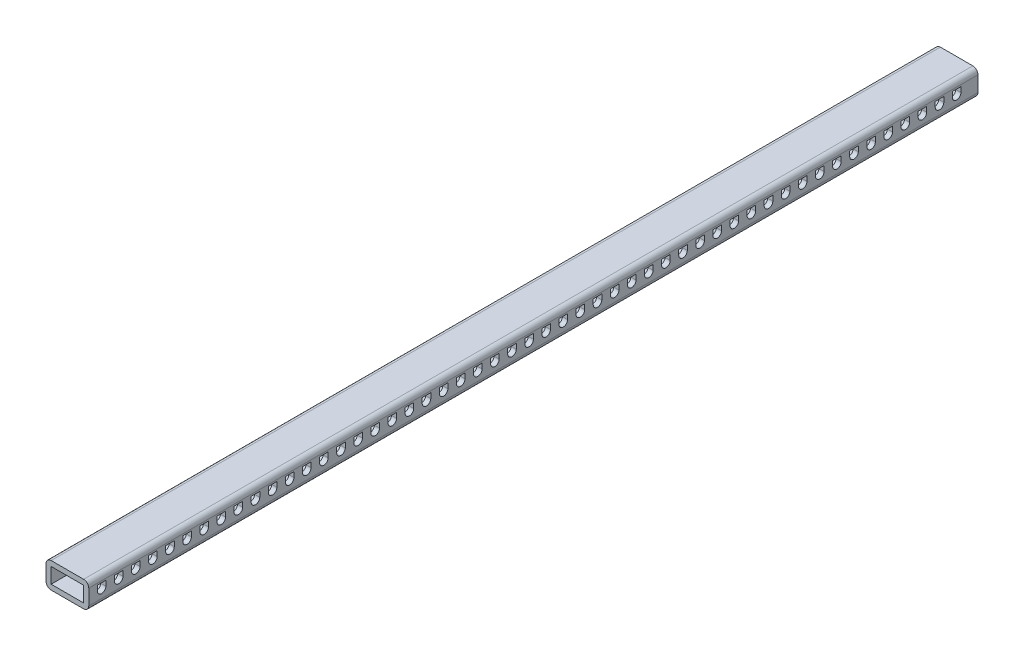
SolidWorks part; units mm, degrees
ref_plane "Front Plane" through (0, 0, 0) normal (0, 0, 1) x (1, 0, 0)
ref_plane "Top Plane" through (0, 0, 0) normal (0, 1, 0) x (1, 0, 0)
ref_plane "Right Plane" through (0, 0, 0) normal (1, 0, 0) x (0, 0, -1)
sketch "Sketch1" plane through (0, 0, 0) normal (0, 0, 1) x (1, 0, 0)
  line L1 (-12.5, 7.5) -> (12.5, 7.5)
  line L2 (-12.5, 7.5) -> (-12.5, -7.5)
  line L3 (-12.5, -7.5) -> (12.5, -7.5)
  line L4 (12.5, 7.5) -> (12.5, -7.5)
  line L5 (-12.5, 7.5) -> (12.5, -7.5) construction
  line L6 (-12.5, -7.5) -> (12.5, 7.5) construction
  point P0 (0, 0)
  dimension "D1" = 25
  dimension "D2" = 15
extrude "Boss-Extrude1" add sketch "Sketch1" along normal blind 520
sketch "Sketch2" plane through (0, 0, 520) normal (0, 0, 1) x (1, 0, 0)
  line L0 (-12.5, 7.5) -> (-12.5, -7.5) construction
  line L1 (-9.5, -4.5) -> (9.5, -4.5)
  line L2 (-9.5, -4.5) -> (-9.5, 4.5)
  line L3 (-9.5, 4.5) -> (9.5, 4.5)
  line L4 (9.5, -4.5) -> (9.5, 4.5)
  line L5 (-9.5, -4.5) -> (9.5, 4.5) construction
  line L6 (-9.5, 4.5) -> (9.5, -4.5) construction
  line L7 (12.5, 7.5) -> (-12.5, 7.5) construction
  point P0 (0, 0)
  dimension "D1" = 3
  dimension "D2" = 3
extrude "Cut-Extrude1" cut sketch "Sketch2" against normal blind 263
sketch "Sketch3" plane through (12.5, 0, 0) normal (1, 0, 0) x (0, 0, -1)
  line L1 (-520, 7.5) -> (0, 7.5) construction
  line L2 (-515, 3.5) -> (-510, 3.5)
  line L3 (-515, 3.5) -> (-515, 0.5)
  line L5 (-510, 3.5) -> (-510, 0.5)
  line L6 (-520, -7.5) -> (-520, 7.5) construction
  line L7 (-507.5, 7.5) -> (-507.5, 3.8883) construction
  line L8 (-505, 3.5) -> (-505, 0.5)
  line L9 (-500, 3.5) -> (-500, 0.5)
  line L10 (-500, 3.5) -> (-505, 3.5)
  line L11 (-497.5, 7.5) -> (-497.5, 3.8883) construction
  line L12 (-487.5, 7.5) -> (-487.5, 3.8883) construction
  line L13 (-495, 3.5) -> (-490, 3.5)
  line L14 (-495, 3.5) -> (-495, 0.5)
  line L15 (-490, 3.5) -> (-490, 0.5)
  line L16 (-485, 3.5) -> (-485, 0.5)
  line L17 (-480, 3.5) -> (-480, 0.5)
  line L18 (-480, 3.5) -> (-485, 3.5)
  line L19 (-477.5, 7.5) -> (-477.5, 3.8883) construction
  line L20 (-467.5, 7.5) -> (-467.5, 3.8883) construction
  line L21 (-485, 3.5) -> (-485, 0.5)
  line L22 (-480, 3.5) -> (-480, 0.5)
  line L23 (-480, 3.5) -> (-485, 3.5)
  line L24 (-475, 3.5) -> (-470, 3.5)
  line L25 (-475, 3.5) -> (-475, 0.5)
  line L26 (-470, 3.5) -> (-470, 0.5)
  line L27 (-465, 3.5) -> (-465, 0.5)
  line L28 (-460, 3.5) -> (-460, 0.5)
  line L29 (-460, 3.5) -> (-465, 3.5)
  line L30 (-457.5, 7.5) -> (-457.5, 3.8883) construction
  line L31 (-447.5, 7.5) -> (-447.5, 3.8883) construction
  line L32 (-437.5, 7.5) -> (-437.5, 3.8883) construction
  line L33 (-427.5, 7.5) -> (-427.5, 3.8883) construction
  line L34 (-465, 3.5) -> (-465, 0.5)
  line L35 (-460, 3.5) -> (-460, 0.5)
  line L36 (-460, 3.5) -> (-465, 3.5)
  line L37 (-455, 3.5) -> (-450, 3.5)
  line L38 (-455, 3.5) -> (-455, 0.5)
  line L39 (-450, 3.5) -> (-450, 0.5)
  line L40 (-455, 3.5) -> (-450, 3.5)
  line L41 (-455, 3.5) -> (-455, 0.5)
  line L42 (-450, 3.5) -> (-450, 0.5)
  line L43 (-445, 3.5) -> (-445, 0.5)
  line L44 (-440, 3.5) -> (-440, 0.5)
  line L45 (-440, 3.5) -> (-445, 3.5)
  line L46 (-435, 3.5) -> (-430, 3.5)
  line L47 (-435, 3.5) -> (-435, 0.5)
  line L48 (-430, 3.5) -> (-430, 0.5)
  line L49 (-425, 3.5) -> (-425, 0.5)
  line L50 (-420, 3.5) -> (-420, 0.5)
  line L51 (-420, 3.5) -> (-425, 3.5)
  line L52 (-417.5, 7.5) -> (-417.5, 3.8883) construction
  line L53 (-407.5, 7.5) -> (-407.5, 3.8883) construction
  line L54 (-397.5, 7.5) -> (-397.5, 3.8883) construction
  line L55 (-387.5, 7.5) -> (-387.5, 3.8883) construction
  line L56 (-377.5, 7.5) -> (-377.5, 3.8883) construction
  line L57 (-367.5, 7.5) -> (-367.5, 3.8883) construction
  line L58 (-357.5, 7.5) -> (-357.5, 3.8883) construction
  line L59 (-347.5, 7.5) -> (-347.5, 3.8883) construction
  line L60 (-425, 3.5) -> (-425, 0.5)
  line L61 (-420, 3.5) -> (-420, 0.5)
  line L62 (-420, 3.5) -> (-425, 3.5)
  line L63 (-415, 3.5) -> (-410, 3.5)
  line L64 (-415, 3.5) -> (-415, 0.5)
  line L65 (-410, 3.5) -> (-410, 0.5)
  line L66 (-405, 3.5) -> (-405, 0.5)
  line L67 (-400, 3.5) -> (-400, 0.5)
  line L68 (-400, 3.5) -> (-405, 3.5)
  line L69 (-405, 3.5) -> (-405, 0.5)
  line L70 (-400, 3.5) -> (-400, 0.5)
  line L71 (-400, 3.5) -> (-405, 3.5)
  line L72 (-395, 3.5) -> (-390, 3.5)
  line L73 (-395, 3.5) -> (-395, 0.5)
  line L74 (-390, 3.5) -> (-390, 0.5)
  line L75 (-395, 3.5) -> (-390, 3.5)
  line L76 (-395, 3.5) -> (-395, 0.5)
  line L77 (-390, 3.5) -> (-390, 0.5)
  line L78 (-385, 3.5) -> (-385, 0.5)
  line L79 (-380, 3.5) -> (-380, 0.5)
  line L80 (-380, 3.5) -> (-385, 3.5)
  line L81 (-375, 3.5) -> (-370, 3.5)
  line L82 (-375, 3.5) -> (-375, 0.5)
  line L83 (-370, 3.5) -> (-370, 0.5)
  line L84 (-375, 3.5) -> (-370, 3.5)
  line L85 (-375, 3.5) -> (-375, 0.5)
  line L86 (-370, 3.5) -> (-370, 0.5)
  line L87 (-365, 3.5) -> (-365, 0.5)
  line L88 (-360, 3.5) -> (-360, 0.5)
  line L89 (-360, 3.5) -> (-365, 3.5)
  line L90 (-355, 3.5) -> (-350, 3.5)
  line L91 (-355, 3.5) -> (-355, 0.5)
  line L92 (-350, 3.5) -> (-350, 0.5)
  line L93 (-345, 3.5) -> (-345, 0.5)
  line L94 (-340, 3.5) -> (-340, 0.5)
  line L95 (-340, 3.5) -> (-345, 3.5)
  line L96 (-345, 3.5) -> (-345, 0.5)
  line L97 (-315, 3.5) -> (-310, 3.5)
  line L98 (-315, 3.5) -> (-315, 0.5)
  line L99 (-310, 3.5) -> (-310, 0.5)
  line L100 (-337.5, 7.5) -> (-337.5, 3.8883) construction
  line L101 (-327.5, 7.5) -> (-327.5, 3.8883) construction
  line L102 (-317.5, 7.5) -> (-317.5, 3.8883) construction
  line L103 (-340, 3.5) -> (-340, 0.5)
  line L104 (-340, 3.5) -> (-345, 3.5)
  line L105 (-335, 3.5) -> (-330, 3.5)
  line L106 (-335, 3.5) -> (-335, 0.5)
  line L107 (-330, 3.5) -> (-330, 0.5)
  line L108 (-325, 3.5) -> (-325, 0.5)
  line L109 (-320, 3.5) -> (-320, 0.5)
  line L110 (-320, 3.5) -> (-325, 3.5)
  line L111 (-325, 3.5) -> (-325, 0.5)
  line L112 (-320, 3.5) -> (-320, 0.5)
  line L113 (-320, 3.5) -> (-325, 3.5)
  line L114 (-307.5, 7.5) -> (-307.5, 3.8883) construction
  line L115 (-315, 3.5) -> (-310, 3.5)
  line L116 (-315, 3.5) -> (-315, 0.5)
  line L117 (-310, 3.5) -> (-310, 0.5)
  line L118 (-315, 3.5) -> (-310, 3.5)
  line L119 (-315, 3.5) -> (-315, 0.5)
  line L120 (-310, 3.5) -> (-310, 0.5)
  line L121 (-305, 3.5) -> (-305, 0.5)
  line L122 (-300, 3.5) -> (-300, 0.5)
  line L123 (-300, 3.5) -> (-305, 3.5)
  arc A0 (-515, 0.5) -> (-510, 0.5) centre (-512.5, 0.5) ccw
  arc A1 (-500, 0.5) -> (-505, 0.5) centre (-502.5, 0.5) cw
  arc A2 (-495, 0.5) -> (-490, 0.5) centre (-492.5, 0.5) ccw
  arc A3 (-480, 0.5) -> (-485, 0.5) centre (-482.5, 0.5) cw
  arc A4 (-480, 0.5) -> (-485, 0.5) centre (-482.5, 0.5) cw
  arc A5 (-475, 0.5) -> (-470, 0.5) centre (-472.5, 0.5) ccw
  arc A6 (-460, 0.5) -> (-465, 0.5) centre (-462.5, 0.5) cw
  arc A7 (-460, 0.5) -> (-465, 0.5) centre (-462.5, 0.5) cw
  arc A8 (-455, 0.5) -> (-450, 0.5) centre (-452.5, 0.5) ccw
  arc A9 (-455, 0.5) -> (-450, 0.5) centre (-452.5, 0.5) ccw
  arc A10 (-440, 0.5) -> (-445, 0.5) centre (-442.5, 0.5) cw
  arc A11 (-435, 0.5) -> (-430, 0.5) centre (-432.5, 0.5) ccw
  arc A12 (-420, 0.5) -> (-425, 0.5) centre (-422.5, 0.5) cw
  arc A13 (-420, 0.5) -> (-425, 0.5) centre (-422.5, 0.5) cw
  arc A14 (-415, 0.5) -> (-410, 0.5) centre (-412.5, 0.5) ccw
  arc A15 (-400, 0.5) -> (-405, 0.5) centre (-402.5, 0.5) cw
  arc A16 (-400, 0.5) -> (-405, 0.5) centre (-402.5, 0.5) cw
  arc A17 (-395, 0.5) -> (-390, 0.5) centre (-392.5, 0.5) ccw
  arc A18 (-395, 0.5) -> (-390, 0.5) centre (-392.5, 0.5) ccw
  arc A19 (-380, 0.5) -> (-385, 0.5) centre (-382.5, 0.5) cw
  arc A20 (-375, 0.5) -> (-370, 0.5) centre (-372.5, 0.5) ccw
  arc A21 (-375, 0.5) -> (-370, 0.5) centre (-372.5, 0.5) ccw
  arc A22 (-360, 0.5) -> (-365, 0.5) centre (-362.5, 0.5) cw
  arc A23 (-355, 0.5) -> (-350, 0.5) centre (-352.5, 0.5) ccw
  arc A24 (-340, 0.5) -> (-345, 0.5) centre (-342.5, 0.5) cw
  arc A25 (-315, 0.5) -> (-310, 0.5) centre (-312.5, 0.5) ccw
  arc A26 (-340, 0.5) -> (-345, 0.5) centre (-342.5, 0.5) cw
  arc A27 (-335, 0.5) -> (-330, 0.5) centre (-332.5, 0.5) ccw
  arc A28 (-320, 0.5) -> (-325, 0.5) centre (-322.5, 0.5) cw
  arc A29 (-320, 0.5) -> (-325, 0.5) centre (-322.5, 0.5) cw
  arc A30 (-315, 0.5) -> (-310, 0.5) centre (-312.5, 0.5) ccw
  arc A31 (-315, 0.5) -> (-310, 0.5) centre (-312.5, 0.5) ccw
  arc A32 (-300, 0.5) -> (-305, 0.5) centre (-302.5, 0.5) cw
  point P18 (-500, 2)
  dimension "D1" = 4
  dimension "D2" = 5
  dimension "D3" = 5
  dimension "D4" = 3
  dimension "D5" = 5
  dimension "D6" = 5
extrude "Cut-Extrude2" cut sketch "Sketch3" against normal blind 263 contours L3 A0 L5 L2 | A1 L9 L10 L8 | L14 A2 L15 L13 | A3 L17 L18 L16 | L25 A5 L26 L24 | A6 L28 L29 L27 | L38 A8 L39 L37 | A10 L44 L45 L43 | L47 A11 L48 L46 | A12 L50 L51 L49 | L64 A14 L65 L63 | A15 L67 L68 L66 | L73 A17 L74 L72 | A19 L79 L80 L78 | L82 A20 L83 L81 | A22 L88 L89 L87 | L91 A23 L92 L90 | A24 L94 L95 L93 | L106 A27 L107 L105 | A28 L109 L110 L108 | L98 A25 L99 L97 | A32 L122 L123 L121
fillet "Fillet1" radius 3 4 edges at (-12.5, -7.5, 260) (12.5, -7.5, 260) (12.5, 7.5, 260) (-12.5, 7.5, 260)
sketch "Sketch7" plane through (12.5, 0, 0) normal (1, 0, 0) x (0, 0, -1)
  line L0 (-297.5, 4.5) -> (-297.5, 1.6532) construction
  line L2 (-300, 0.5) -> (-300, 3.5)
  line L3 (-300, 3.5) -> (-305, 3.5)
  line L4 (-305, 0.5) -> (-305, 3.5)
  line L5 (-300, -2.5) -> (-305, 3.5) construction
  line L6 (-300, 3.5) -> (-305, -2.5) construction
  line L7 (0, 4.5) -> (-520, 4.5) construction
  line L8 (-295, 3.5) -> (-290, -2.5) construction
  line L9 (-295, -2.5) -> (-290, 3.5) construction
  line L10 (-290, 0.5) -> (-290, 3.5)
  line L11 (-295, 3.5) -> (-290, 3.5)
  line L12 (-295, 0.5) -> (-295, 3.5)
  line L13 (-287.5, 4.5) -> (-287.5, 0.5) construction
  line L14 (-280, -2.5) -> (-285, 3.5) construction
  line L15 (-280, 3.5) -> (-285, -2.5) construction
  line L16 (-275, 3.5) -> (-270, -2.5) construction
  line L17 (-275, -2.5) -> (-270, 3.5) construction
  line L18 (-277.5, 4.5) -> (-277.5, 1.6532) construction
  line L19 (-280, 0.5) -> (-280, 3.5)
  line L20 (-280, 3.5) -> (-285, 3.5)
  line L21 (-285, 0.5) -> (-285, 3.5)
  line L22 (-270, 0.5) -> (-270, 3.5)
  line L23 (-275, 3.5) -> (-270, 3.5)
  line L24 (-275, 0.5) -> (-275, 3.5)
  line L25 (-275, 3.5) -> (-270, -2.5) construction
  line L26 (-275, -2.5) -> (-270, 3.5) construction
  line L27 (-267.5, 4.5) -> (-267.5, 0.5) construction
  line L28 (-260, -2.5) -> (-265, 3.5) construction
  line L29 (-260, 3.5) -> (-265, -2.5) construction
  line L30 (-255, 3.5) -> (-250, -2.5) construction
  line L31 (-255, -2.5) -> (-250, 3.5) construction
  line L32 (-257.5, 4.5) -> (-257.5, 1.6532) construction
  line L33 (-270, 0.5) -> (-270, 3.5)
  line L34 (-275, 3.5) -> (-270, 3.5)
  line L35 (-275, 0.5) -> (-275, 3.5)
  line L36 (-260, 0.5) -> (-260, 3.5)
  line L37 (-260, 3.5) -> (-265, 3.5)
  line L38 (-265, 0.5) -> (-265, 3.5)
  line L39 (-250, 0.5) -> (-250, 3.5)
  line L40 (-255, 3.5) -> (-250, 3.5)
  line L41 (-255, 0.5) -> (-255, 3.5)
  line L42 (-255, 3.5) -> (-250, -2.5) construction
  line L43 (-255, -2.5) -> (-250, 3.5) construction
  line L44 (-247.5, 4.5) -> (-247.5, 0.5) construction
  line L45 (-240, -2.5) -> (-245, 3.5) construction
  line L46 (-240, 3.5) -> (-245, -2.5) construction
  line L47 (-237.5, 4.5) -> (-237.5, 1.6532) construction
  line L48 (-240, -2.5) -> (-245, 3.5) construction
  line L49 (-240, 3.5) -> (-245, -2.5) construction
  line L50 (-235, 3.5) -> (-230, -2.5) construction
  line L51 (-235, -2.5) -> (-230, 3.5) construction
  line L52 (-227.5, 4.5) -> (-227.5, 0.5) construction
  line L53 (-220, -2.5) -> (-225, 3.5) construction
  line L54 (-220, 3.5) -> (-225, -2.5) construction
  line L55 (-215, 3.5) -> (-210, -2.5) construction
  line L56 (-215, -2.5) -> (-210, 3.5) construction
  line L57 (-217.5, 4.5) -> (-217.5, 1.6532) construction
  line L58 (-250, 0.5) -> (-250, 3.5)
  line L59 (-255, 3.5) -> (-250, 3.5)
  line L60 (-255, 0.5) -> (-255, 3.5)
  line L61 (-240, 0.5) -> (-240, 3.5)
  line L62 (-240, 3.5) -> (-245, 3.5)
  line L63 (-245, 0.5) -> (-245, 3.5)
  line L64 (-240, 0.5) -> (-240, 3.5)
  line L65 (-240, 3.5) -> (-245, 3.5)
  line L66 (-245, 0.5) -> (-245, 3.5)
  line L67 (-230, 0.5) -> (-230, 3.5)
  line L68 (-235, 3.5) -> (-230, 3.5)
  line L69 (-235, 0.5) -> (-235, 3.5)
  line L70 (-220, 0.5) -> (-220, 3.5)
  line L71 (-220, 3.5) -> (-225, 3.5)
  line L72 (-225, 0.5) -> (-225, 3.5)
  line L73 (-210, 0.5) -> (-210, 3.5)
  line L74 (-215, 3.5) -> (-210, 3.5)
  line L75 (-215, 0.5) -> (-215, 3.5)
  line L76 (-215, 3.5) -> (-210, -2.5) construction
  line L77 (-215, -2.5) -> (-210, 3.5) construction
  line L78 (-207.5, 4.5) -> (-207.5, 0.5) construction
  line L79 (-200, -2.5) -> (-205, 3.5) construction
  line L80 (-200, 3.5) -> (-205, -2.5) construction
  line L81 (-195, 3.5) -> (-190, -2.5) construction
  line L82 (-195, -2.5) -> (-190, 3.5) construction
  line L83 (-197.5, 4.5) -> (-197.5, 1.6532) construction
  line L84 (-195, 3.5) -> (-190, -2.5) construction
  line L85 (-195, -2.5) -> (-190, 3.5) construction
  line L86 (-187.5, 4.5) -> (-187.5, 0.5) construction
  line L87 (-180, -2.5) -> (-185, 3.5) construction
  line L88 (-180, 3.5) -> (-185, -2.5) construction
  line L89 (-177.5, 4.5) -> (-177.5, 1.6532) construction
  line L90 (-180, -2.5) -> (-185, 3.5) construction
  line L91 (-180, 3.5) -> (-185, -2.5) construction
  line L92 (-175, 3.5) -> (-170, -2.5) construction
  line L93 (-175, -2.5) -> (-170, 3.5) construction
  line L94 (-167.5, 4.5) -> (-167.5, 0.5) construction
  line L95 (-160, -2.5) -> (-165, 3.5) construction
  line L96 (-160, 3.5) -> (-165, -2.5) construction
  line L97 (-157.5, 4.5) -> (-157.5, 1.6532) construction
  line L98 (-160, -2.5) -> (-165, 3.5) construction
  line L99 (-160, 3.5) -> (-165, -2.5) construction
  line L100 (-155, 3.5) -> (-150, -2.5) construction
  line L101 (-155, -2.5) -> (-150, 3.5) construction
  line L102 (-147.5, 4.5) -> (-147.5, 0.5) construction
  line L103 (-140, -2.5) -> (-145, 3.5) construction
  line L104 (-140, 3.5) -> (-145, -2.5) construction
  line L105 (-135, 3.5) -> (-130, -2.5) construction
  line L106 (-135, -2.5) -> (-130, 3.5) construction
  line L107 (-137.5, 4.5) -> (-137.5, 1.6532) construction
  line L108 (-210, 0.5) -> (-210, 3.5)
  line L109 (-215, 3.5) -> (-210, 3.5)
  line L110 (-215, 0.5) -> (-215, 3.5)
  line L111 (-200, 0.5) -> (-200, 3.5)
  line L112 (-200, 3.5) -> (-205, 3.5)
  line L113 (-205, 0.5) -> (-205, 3.5)
  line L114 (-190, 0.5) -> (-190, 3.5)
  line L115 (-195, 3.5) -> (-190, 3.5)
  line L116 (-195, 0.5) -> (-195, 3.5)
  line L117 (-190, 0.5) -> (-190, 3.5)
  line L118 (-195, 3.5) -> (-190, 3.5)
  line L119 (-195, 0.5) -> (-195, 3.5)
  line L120 (-180, 0.5) -> (-180, 3.5)
  line L121 (-180, 3.5) -> (-185, 3.5)
  line L122 (-185, 0.5) -> (-185, 3.5)
  line L123 (-180, 0.5) -> (-180, 3.5)
  line L124 (-180, 3.5) -> (-185, 3.5)
  line L125 (-185, 0.5) -> (-185, 3.5)
  line L126 (-170, 0.5) -> (-170, 3.5)
  line L127 (-175, 3.5) -> (-170, 3.5)
  line L128 (-175, 0.5) -> (-175, 3.5)
  line L129 (-160, 0.5) -> (-160, 3.5)
  line L130 (-160, 3.5) -> (-165, 3.5)
  line L131 (-165, 0.5) -> (-165, 3.5)
  line L132 (-160, 0.5) -> (-160, 3.5)
  line L133 (-160, 3.5) -> (-165, 3.5)
  line L134 (-165, 0.5) -> (-165, 3.5)
  line L135 (-150, 0.5) -> (-150, 3.5)
  line L136 (-155, 3.5) -> (-150, 3.5)
  line L137 (-155, 0.5) -> (-155, 3.5)
  line L138 (-140, 0.5) -> (-140, 3.5)
  line L139 (-140, 3.5) -> (-145, 3.5)
  line L140 (-145, 0.5) -> (-145, 3.5)
  line L141 (-130, 0.5) -> (-130, 3.5)
  line L142 (-135, 3.5) -> (-130, 3.5)
  line L143 (-135, 0.5) -> (-135, 3.5)
  line L144 (-135, 3.5) -> (-130, -2.5) construction
  line L145 (-135, -2.5) -> (-130, 3.5) construction
  line L146 (-127.5, 4.5) -> (-127.5, 0.5) construction
  line L147 (-120, -2.5) -> (-125, 3.5) construction
  line L148 (-120, 3.5) -> (-125, -2.5) construction
  line L149 (-115, 3.5) -> (-110, -2.5) construction
  line L150 (-115, -2.5) -> (-110, 3.5) construction
  line L151 (-117.5, 4.5) -> (-117.5, 1.6532) construction
  line L152 (-115, 3.5) -> (-110, -2.5) construction
  line L153 (-115, -2.5) -> (-110, 3.5) construction
  line L154 (-107.5, 4.5) -> (-107.5, 0.5) construction
  line L155 (-100, -2.5) -> (-105, 3.5) construction
  line L156 (-100, 3.5) -> (-105, -2.5) construction
  line L157 (-95, 3.5) -> (-90, -2.5) construction
  line L158 (-95, -2.5) -> (-90, 3.5) construction
  line L159 (-97.5, 4.5) -> (-97.5, 1.6532) construction
  line L160 (-95, 3.5) -> (-90, -2.5) construction
  line L161 (-95, -2.5) -> (-90, 3.5) construction
  line L162 (-87.5, 4.5) -> (-87.5, 0.5) construction
  line L163 (-80, -2.5) -> (-85, 3.5) construction
  line L164 (-80, 3.5) -> (-85, -2.5) construction
  line L165 (-77.5, 4.5) -> (-77.5, 1.6532) construction
  line L166 (-80, -2.5) -> (-85, 3.5) construction
  line L167 (-80, 3.5) -> (-85, -2.5) construction
  line L168 (-75, 3.5) -> (-70, -2.5) construction
  line L169 (-75, -2.5) -> (-70, 3.5) construction
  line L170 (-130, 0.5) -> (-130, 3.5)
  line L171 (-135, 3.5) -> (-130, 3.5)
  line L172 (-135, 0.5) -> (-135, 3.5)
  line L173 (-120, 0.5) -> (-120, 3.5)
  line L174 (-120, 3.5) -> (-125, 3.5)
  line L175 (-125, 0.5) -> (-125, 3.5)
  line L176 (-110, 0.5) -> (-110, 3.5)
  line L177 (-115, 3.5) -> (-110, 3.5)
  line L178 (-115, 0.5) -> (-115, 3.5)
  line L179 (-110, 0.5) -> (-110, 3.5)
  line L180 (-115, 3.5) -> (-110, 3.5)
  line L181 (-115, 0.5) -> (-115, 3.5)
  line L182 (-100, 0.5) -> (-100, 3.5)
  line L183 (-100, 3.5) -> (-105, 3.5)
  line L184 (-105, 0.5) -> (-105, 3.5)
  line L185 (-90, 0.5) -> (-90, 3.5)
  line L186 (-95, 3.5) -> (-90, 3.5)
  line L187 (-95, 0.5) -> (-95, 3.5)
  line L188 (-90, 0.5) -> (-90, 3.5)
  line L189 (-95, 3.5) -> (-90, 3.5)
  line L190 (-95, 0.5) -> (-95, 3.5)
  line L191 (-80, 0.5) -> (-80, 3.5)
  line L192 (-80, 3.5) -> (-85, 3.5)
  line L193 (-85, 0.5) -> (-85, 3.5)
  line L194 (-80, 0.5) -> (-80, 3.5)
  line L195 (-80, 3.5) -> (-85, 3.5)
  line L196 (-85, 0.5) -> (-85, 3.5)
  line L197 (-70, 0.5) -> (-70, 3.5)
  line L198 (-75, 3.5) -> (-70, 3.5)
  line L199 (-75, 0.5) -> (-75, 3.5)
  line L200 (-75, 3.5) -> (-70, -2.5) construction
  line L201 (-75, -2.5) -> (-70, 3.5) construction
  line L202 (-75, 3.5) -> (-70, -2.5) construction
  line L203 (-75, -2.5) -> (-70, 3.5) construction
  line L204 (-67.5, 4.5) -> (-67.5, 0.5) construction
  line L205 (-60, -2.5) -> (-65, 3.5) construction
  line L206 (-60, 3.5) -> (-65, -2.5) construction
  line L207 (-57.5, 4.5) -> (-57.5, 1.6532) construction
  line L208 (-60, -2.5) -> (-65, 3.5) construction
  line L209 (-60, 3.5) -> (-65, -2.5) construction
  line L210 (-55, 3.5) -> (-50, -2.5) construction
  line L211 (-55, -2.5) -> (-50, 3.5) construction
  line L212 (-47.5, 4.5) -> (-47.5, 0.5) construction
  line L213 (-40, -2.5) -> (-45, 3.5) construction
  line L214 (-40, 3.5) -> (-45, -2.5) construction
  line L215 (-37.5, 4.5) -> (-37.5, 1.6532) construction
  line L216 (-40, -2.5) -> (-45, 3.5) construction
  line L217 (-40, 3.5) -> (-45, -2.5) construction
  line L218 (-35, 3.5) -> (-30, -2.5) construction
  line L219 (-35, -2.5) -> (-30, 3.5) construction
  line L220 (-27.5, 4.5) -> (-27.5, 0.5) construction
  line L221 (-20, -2.5) -> (-25, 3.5) construction
  line L222 (-20, 3.5) -> (-25, -2.5) construction
  line L223 (-17.5, 4.5) -> (-17.5, 1.6532) construction
  line L224 (-20, -2.5) -> (-25, 3.5) construction
  line L225 (-20, 3.5) -> (-25, -2.5) construction
  line L226 (-70, 0.5) -> (-70, 3.5)
  line L227 (-75, 3.5) -> (-70, 3.5)
  line L228 (-75, 0.5) -> (-75, 3.5)
  line L229 (-70, 0.5) -> (-70, 3.5)
  line L230 (-75, 3.5) -> (-70, 3.5)
  line L231 (-75, 0.5) -> (-75, 3.5)
  line L232 (-60, 0.5) -> (-60, 3.5)
  line L233 (-60, 3.5) -> (-65, 3.5)
  line L234 (-65, 0.5) -> (-65, 3.5)
  line L235 (-60, 0.5) -> (-60, 3.5)
  line L236 (-60, 3.5) -> (-65, 3.5)
  line L237 (-65, 0.5) -> (-65, 3.5)
  line L238 (-50, 0.5) -> (-50, 3.5)
  line L239 (-55, 3.5) -> (-50, 3.5)
  line L240 (-55, 0.5) -> (-55, 3.5)
  line L241 (-40, 0.5) -> (-40, 3.5)
  line L242 (-40, 3.5) -> (-45, 3.5)
  line L243 (-45, 0.5) -> (-45, 3.5)
  line L244 (-40, 0.5) -> (-40, 3.5)
  line L245 (-40, 3.5) -> (-45, 3.5)
  line L246 (-45, 0.5) -> (-45, 3.5)
  line L247 (-30, 0.5) -> (-30, 3.5)
  line L248 (-35, 3.5) -> (-30, 3.5)
  line L249 (-35, 0.5) -> (-35, 3.5)
  line L250 (-20, 0.5) -> (-20, 3.5)
  line L251 (-20, 3.5) -> (-25, 3.5)
  line L252 (-25, 0.5) -> (-25, 3.5)
  line L253 (-20, 0.5) -> (-20, 3.5)
  line L254 (-20, 3.5) -> (-25, 3.5)
  line L255 (-25, 0.5) -> (-25, 3.5)
  line L256 (-15, 3.5) -> (-10, -2.5) construction
  line L257 (-15, -2.5) -> (-10, 3.5) construction
  line L258 (-15, 3.5) -> (-10, -2.5) construction
  line L259 (-15, -2.5) -> (-10, 3.5) construction
  line L260 (-10, 0.5) -> (-10, 3.5)
  line L261 (-15, 3.5) -> (-10, 3.5)
  line L262 (-15, 0.5) -> (-15, 3.5)
  line L263 (-10, 0.5) -> (-10, 3.5)
  line L264 (-15, 3.5) -> (-10, 3.5)
  line L265 (-15, 0.5) -> (-15, 3.5)
  arc A0 (-305, 0.5) -> (-300, 0.5) centre (-302.5, 0.5) ccw
  arc A1 (-290, 0.5) -> (-295, 0.5) centre (-292.5, 0.5) cw
  arc A2 (-285, 0.5) -> (-280, 0.5) centre (-282.5, 0.5) ccw
  arc A3 (-270, 0.5) -> (-275, 0.5) centre (-272.5, 0.5) cw
  arc A4 (-270, 0.5) -> (-275, 0.5) centre (-272.5, 0.5) cw
  arc A5 (-265, 0.5) -> (-260, 0.5) centre (-262.5, 0.5) ccw
  arc A6 (-250, 0.5) -> (-255, 0.5) centre (-252.5, 0.5) cw
  arc A7 (-250, 0.5) -> (-255, 0.5) centre (-252.5, 0.5) cw
  arc A8 (-245, 0.5) -> (-240, 0.5) centre (-242.5, 0.5) ccw
  arc A9 (-245, 0.5) -> (-240, 0.5) centre (-242.5, 0.5) ccw
  arc A10 (-230, 0.5) -> (-235, 0.5) centre (-232.5, 0.5) cw
  arc A11 (-225, 0.5) -> (-220, 0.5) centre (-222.5, 0.5) ccw
  arc A12 (-210, 0.5) -> (-215, 0.5) centre (-212.5, 0.5) cw
  arc A13 (-210, 0.5) -> (-215, 0.5) centre (-212.5, 0.5) cw
  arc A14 (-205, 0.5) -> (-200, 0.5) centre (-202.5, 0.5) ccw
  arc A15 (-190, 0.5) -> (-195, 0.5) centre (-192.5, 0.5) cw
  arc A16 (-190, 0.5) -> (-195, 0.5) centre (-192.5, 0.5) cw
  arc A17 (-185, 0.5) -> (-180, 0.5) centre (-182.5, 0.5) ccw
  arc A18 (-185, 0.5) -> (-180, 0.5) centre (-182.5, 0.5) ccw
  arc A19 (-170, 0.5) -> (-175, 0.5) centre (-172.5, 0.5) cw
  arc A20 (-165, 0.5) -> (-160, 0.5) centre (-162.5, 0.5) ccw
  arc A21 (-165, 0.5) -> (-160, 0.5) centre (-162.5, 0.5) ccw
  arc A22 (-150, 0.5) -> (-155, 0.5) centre (-152.5, 0.5) cw
  arc A23 (-145, 0.5) -> (-140, 0.5) centre (-142.5, 0.5) ccw
  arc A24 (-130, 0.5) -> (-135, 0.5) centre (-132.5, 0.5) cw
  arc A25 (-130, 0.5) -> (-135, 0.5) centre (-132.5, 0.5) cw
  arc A26 (-125, 0.5) -> (-120, 0.5) centre (-122.5, 0.5) ccw
  arc A27 (-110, 0.5) -> (-115, 0.5) centre (-112.5, 0.5) cw
  arc A28 (-110, 0.5) -> (-115, 0.5) centre (-112.5, 0.5) cw
  arc A29 (-105, 0.5) -> (-100, 0.5) centre (-102.5, 0.5) ccw
  arc A30 (-90, 0.5) -> (-95, 0.5) centre (-92.5, 0.5) cw
  arc A31 (-90, 0.5) -> (-95, 0.5) centre (-92.5, 0.5) cw
  arc A32 (-85, 0.5) -> (-80, 0.5) centre (-82.5, 0.5) ccw
  arc A33 (-85, 0.5) -> (-80, 0.5) centre (-82.5, 0.5) ccw
  arc A34 (-70, 0.5) -> (-75, 0.5) centre (-72.5, 0.5) cw
  arc A35 (-70, 0.5) -> (-75, 0.5) centre (-72.5, 0.5) cw
  arc A36 (-70, 0.5) -> (-75, 0.5) centre (-72.5, 0.5) cw
  arc A37 (-65, 0.5) -> (-60, 0.5) centre (-62.5, 0.5) ccw
  arc A38 (-65, 0.5) -> (-60, 0.5) centre (-62.5, 0.5) ccw
  arc A39 (-50, 0.5) -> (-55, 0.5) centre (-52.5, 0.5) cw
  arc A40 (-45, 0.5) -> (-40, 0.5) centre (-42.5, 0.5) ccw
  arc A41 (-45, 0.5) -> (-40, 0.5) centre (-42.5, 0.5) ccw
  arc A42 (-30, 0.5) -> (-35, 0.5) centre (-32.5, 0.5) cw
  arc A43 (-25, 0.5) -> (-20, 0.5) centre (-22.5, 0.5) ccw
  arc A44 (-25, 0.5) -> (-20, 0.5) centre (-22.5, 0.5) ccw
  arc A45 (-10, 0.5) -> (-15, 0.5) centre (-12.5, 0.5) cw
  arc A46 (-10, 0.5) -> (-15, 0.5) centre (-12.5, 0.5) cw
  dimension "D1" = 5
  dimension "D2" = 5
  dimension "D3" = 5
extrude "Cut-Extrude6" cut sketch "Sketch7" against normal blind 29 contours A1 L10 L11 L12 | L21 A2 L19 L20 | A3 L22 L23 L24 | L38 A5 L36 L37 | A6 L39 L40 L41 | L63 A8 L61 L62 | A10 L67 L68 L69 | L72 A11 L70 L71 | A12 L73 L74 L75 | L113 A14 L111 L112 | A15 L114 L115 L116 | L122 A17 L120 L121 | A19 L126 L127 L128 | L131 A20 L129 L130 | A22 L135 L136 L137 | L140 A23 L138 L139 | A24 L141 L142 L143 | L175 A26 L173 L174 | A27 L176 L177 L178 | L184 A29 L182 L183 | A30 L185 L186 L187 | L193 A32 L191 L192 | A34 L197 L198 L199 | L234 A37 L232 L233 | A39 L238 L239 L240 | L243 A40 L241 L242 | A42 L247 L248 L249 | L252 A43 L250 L251 | A45 L260 L261 L262
sketch "Sketch8" plane through (0, 0, 0) normal (0, 0, -1) x (-1, 0, 0)
  line L0 (-9.5, 7.5) -> (9.5, 7.5) construction
  line L1 (9.5, -4.5) -> (-9.5, -4.5)
  line L2 (9.5, -4.5) -> (9.5, 4.5)
  line L3 (9.5, 4.5) -> (-9.5, 4.5)
  line L4 (-9.5, -4.5) -> (-9.5, 4.5)
  line L5 (9.5, -4.5) -> (-9.5, 4.5) construction
  line L6 (9.5, 4.5) -> (-9.5, -4.5) construction
  line L7 (-12.5, -4.5) -> (-12.5, 4.5) construction
  point P0 (0, 0)
  dimension "D1" = 3
  dimension "D2" = 3
extrude "Cut-Extrude7" cut sketch "Sketch8" against normal blind 535
